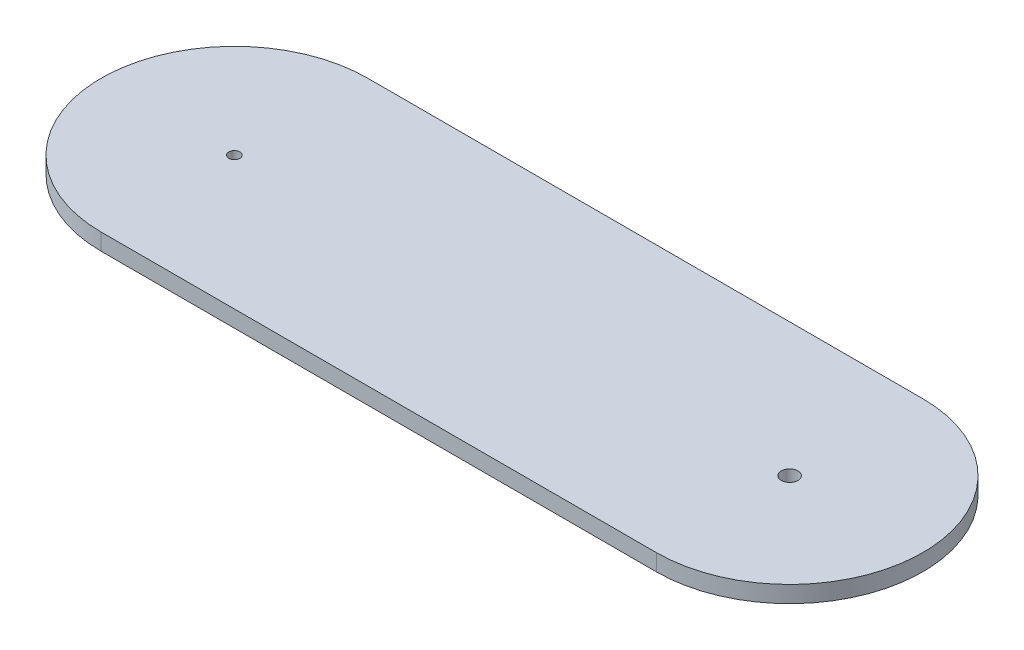
SolidWorks part; units mm, degrees
ref_plane "Front Plane" through (0, 0, 0) normal (0, 0, 1) x (1, 0, 0)
ref_plane "Top Plane" through (0, 0, 0) normal (0, 1, 0) x (1, 0, 0)
ref_plane "Right Plane" through (0, 0, 0) normal (1, 0, 0) x (0, 0, -1)
sketch "Sketch1" plane through (0, 0, 0) normal (0, 1, 0) x (1, 0, 0)
  line L0 (0, 24) -> (100, 24)
  line L2 (100, -24) -> (0, -24)
  arc A0 (0, 24) -> (0, -24) centre (0, 0) ccw
  arc A1 (100, 24) -> (100, -24) centre (100, 0) cw
  dimension "D1" = 48
  dimension "D4" = 24
  dimension "D2" = 48
  dimension "D3" = 100
extrude "Boss-Extrude1" add sketch "Sketch1" along normal blind 3
sketch "Sketch2" plane through (0, 3, 0) normal (0, 1, 0) x (1, 0, 0)
  circle A0 centre (0, 0) radius 1
  arc A1 (0, 24) -> (0, -24) centre (0, 0) ccw construction
  dimension "D1" = 2
extrude "Cut-Extrude1" cut sketch "Sketch2" against normal blind 3
sketch "Sketch3" plane through (0, 3, 0) normal (0, 1, 0) x (1, 0, 0)
  line L0 (105.3442, 2.5) -> (105.9042, 2.5)
  line L2 (105.9042, -2.5) -> (105.3442, -2.5)
  arc A0 (105.3442, 2.5) -> (105.3442, -2.5) centre (100, 0) ccw
  arc A1 (100, -24) -> (100, 24) centre (100, 0) ccw construction
  arc A2 (105.9042, 2.5) -> (105.9042, -2.5) centre (105.9042, 0) cw
  dimension "D1" = 11.8
  dimension "D2" = 2.5
  dimension "D3" = 0.56
sketch "Sketch4" plane through (0, 3, 0) normal (0, 1, 0) x (1, 0, 0)
  circle A0 centre (100, 0) radius 1.5
  dimension "D1" = 3
extrude "Cut-Extrude2" cut sketch "Sketch4" against normal blind 10
